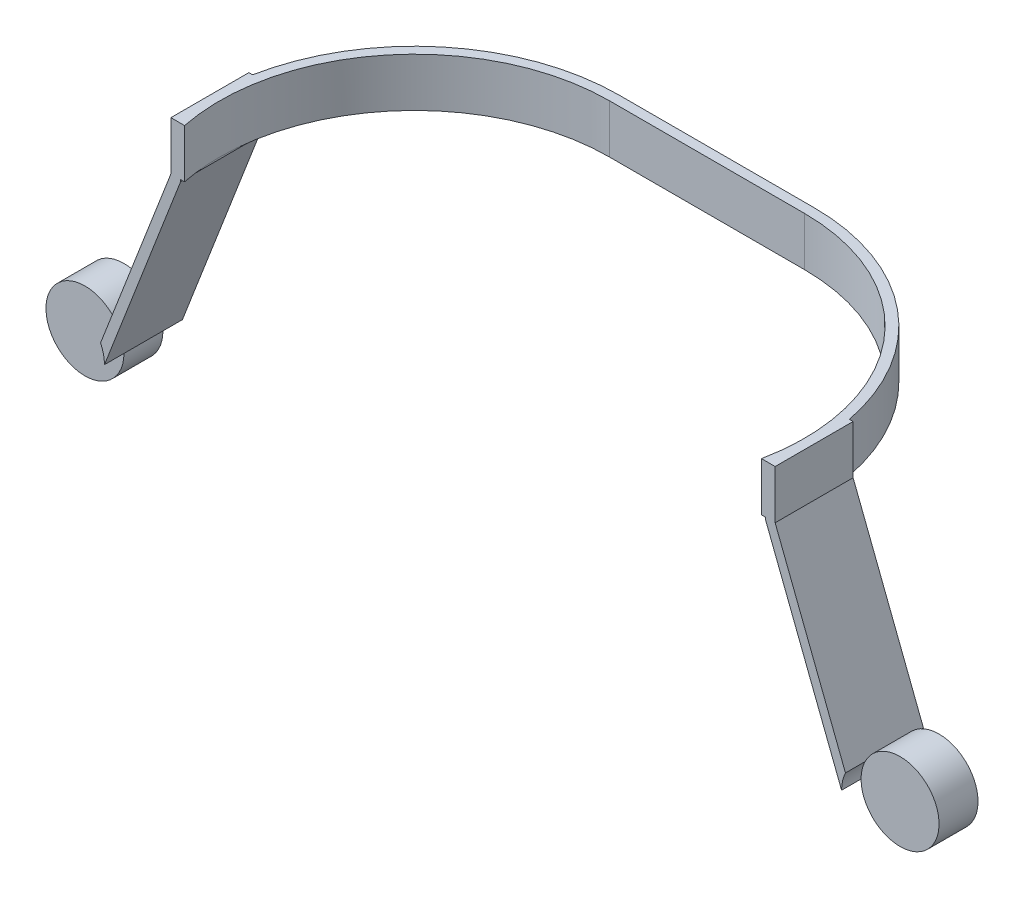
SolidWorks part; units mm, degrees
ref_plane "Front" through (0, 0, 0) normal (0, 0, 1) x (1, 0, 0)
ref_plane "Top" through (0, 0, 0) normal (0, 1, 0) x (1, 0, 0)
ref_plane "Right" through (0, 0, 0) normal (1, 0, 0) x (0, 0, -1)
sketch "草图2" plane through (0, 0, 0) normal (0, 1, 0) x (1, 0, 0)
  line L0 (-40, 0) -> (40, 0) construction
  line L1 (-40, 80) -> (40, 80)
  line L2 (-40, -80) -> (40, -80)
  line L3 (-40, 0) -> (40, 0) construction
  line L4 (-40, 84) -> (40, 84)
  line L5 (-40, -84) -> (40, -84)
  arc A0 (-40, 80) -> (-40, -80) centre (-40, 0) ccw
  arc A1 (40, -80) -> (40, 80) centre (40, 0) ccw
  arc A2 (-40, 84) -> (-40, -84) centre (-40, 0) ccw
  arc A3 (40, -84) -> (40, 84) centre (40, 0) ccw
  point P2 (0, 0)
  point P10 (0, 0)
extrude "凸台-拉伸1" add sketch "草图2" along normal blind 20
sketch "草图8" plane through (0, 20, 0) normal (0, 1, 0) x (1, 0, 0)
  line L0 (0, 0) -> (-175.2062, 0) construction
  line L1 (-124, 16) -> (-120, 16)
  line L2 (-124, 16) -> (-124, -16)
  line L3 (-124, -16) -> (-120, -16)
  line L4 (-120, 16) -> (-120, -16)
  dimension "D1" = 4
  dimension "D2" = 32
  dimension "D3" = 16
sketch "草图9" plane through (0, 0, 0) normal (0, 0, 1) x (1, 0, 0)
  line L0 (0, 0) -> (-176.3582, 0) construction
  line L1 (-155, -80) -> (155, -80) construction
  line L2 (0, 0) -> (0, -149.7853) construction
  line L3 (-124, 20) -> (-124, 0)
  line L4 (-124, 0) -> (-155, -80)
  point P11 (155, -80)
  dimension "D1" = 80
  dimension "D2" = 310
  dimension "D3" = 155
sweep "扫描1" add profiles "草图8" path "草图9"
sketch "草图11" plane through (0, 20, 0) normal (0, 1, 0) x (1, 0, 0)
  line L0 (0, 0) -> (130.9327, 0) construction
  line L1 (0, 0) -> (0, 51.5924) construction
  line L3 (124, 16) -> (120, 16)
  line L4 (124, 16) -> (124, -16)
  line L5 (124, -16) -> (120, -16)
  line L6 (120, 16) -> (120, -16)
  dimension "D1" = 124
  dimension "D2" = 4
  dimension "D3" = 32
  dimension "D4" = 16
sketch "草图12" plane through (0, 0, 0) normal (0, 0, 1) x (1, 0, 0)
  line L0 (0, 0) -> (0, -98.1424) construction
  line L1 (-155, -80) -> (155, -80) construction
  line L2 (124, 20) -> (124, 0)
  line L3 (124, 0) -> (155, -80)
  dimension "D1" = 310
sweep "扫描2" add profiles "草图11" path "草图12"
sketch "草图13" plane through (0, 0, 16) normal (0, 0, 1) x (1, 0, 0)
  line L0 (-151.2702, -81.4453) -> (-167.2702, -81.4453) construction
  line L1 (151.2702, -81.4453) -> (167.2702, -81.4453) construction
  circle A0 centre (-167.2702, -81.4453) radius 16
  circle A1 centre (167.2702, -81.4453) radius 16
extrude "切除-拉伸4" cut sketch "草图13" against normal through all
sketch "草图16" plane through (0, 0, 0) normal (0, 0, 1) x (1, 0, 0)
  circle A0 centre (167.2702, -81.4453) radius 16
  circle A1 centre (-167.2702, -81.4453) radius 16
extrude "凸台-拉伸4" add sketch "草图16" along normal mid plane 16
sketch "草图17" plane through (0, 20, 0) normal (0, 1, 0) x (1, 0, 0)
  line L1 (-124, -16) -> (152.6561, -16)
  line L2 (-124, -16) -> (-124, -89.6615)
  line L3 (-124, -89.6615) -> (152.6561, -89.6615)
  line L4 (152.6561, -16) -> (152.6561, -89.6615)
extrude "切除-拉伸5" cut sketch "草图17" against normal through all
